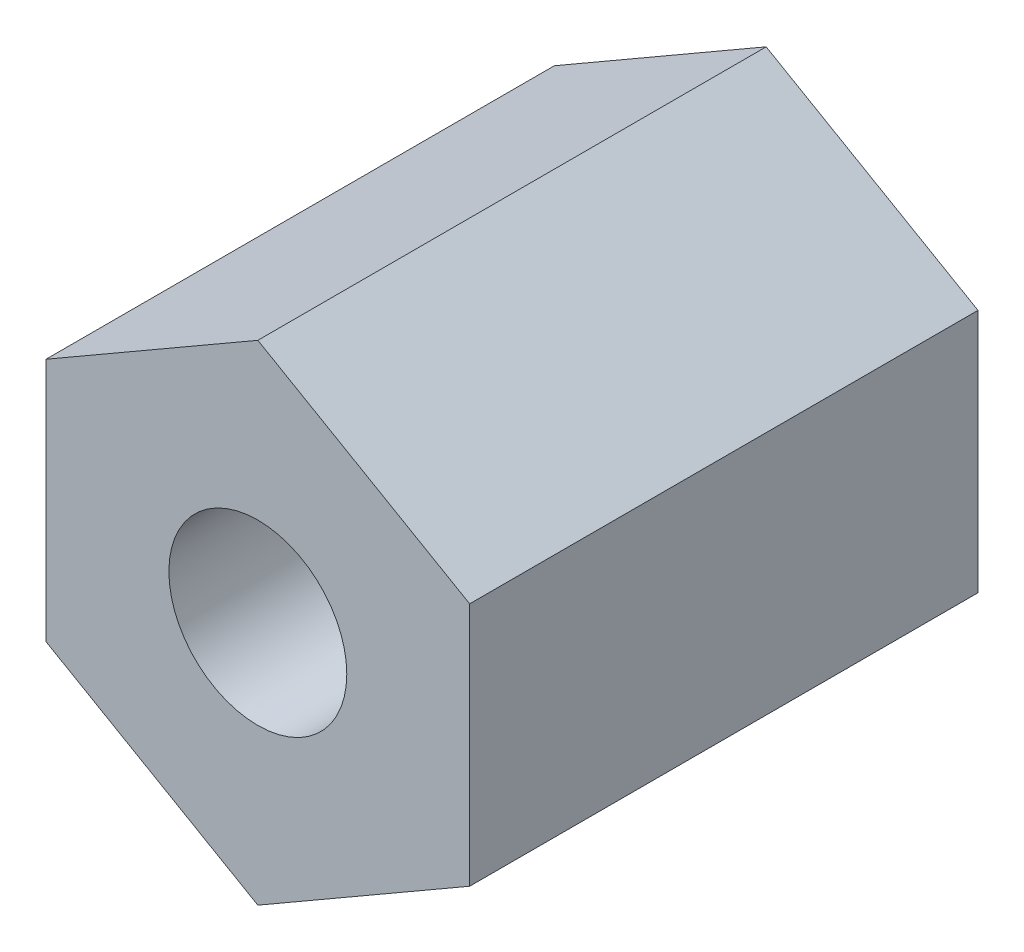
SolidWorks part; units mm, degrees
material "Latón"
ref_plane "Alzado" through (0, 0, 0) normal (0, 0, 1) x (1, 0, 0)
ref_plane "Planta" through (0, 0, 0) normal (0, 1, 0) x (1, 0, 0)
ref_plane "Vista lateral" through (0, 0, 0) normal (1, 0, 0) x (0, 0, -1)
sketch "Croquis1" plane through (0, 0, 0) normal (0, 0, 1) x (1, 0, 0)
  line L0 (-105.9998, -54.5565) -> (-108.5, -53.113)
  line L1 (-108.5, -53.113) -> (-111.0002, -54.5565)
  line L2 (-111.0002, -54.5565) -> (-111.0002, -57.4435)
  line L3 (-111.0002, -57.4435) -> (-108.5, -58.887)
  line L4 (-108.5, -58.887) -> (-105.9998, -57.4435)
  line L5 (-105.9998, -57.4435) -> (-105.9998, -54.5565)
  dimension "D1" = 105.9998
  dimension "D2" = 54.5565
  dimension "D3" = 108.5
  dimension "D4" = 53.113
  dimension "D5" = 111.0002
  dimension "D6" = 54.5565
  dimension "D7" = 111.0002
  dimension "D8" = 57.4435
  dimension "D9" = 108.5
  dimension "D10" = 58.887
  dimension "D11" = 105.9998
  dimension "D12" = 57.4435
extrude "Hex_5" add sketch "Croquis1" along normal blind 6 from offset 12.7
sketch "Croquis2" plane through (0, 0, 0) normal (0, 0, 1) x (1, 0, 0)
  circle A0 centre (-108.5, -56) radius 1.05
  dimension "D1" = 2.1
  dimension "D2" = 108.5
  dimension "D3" = 56
extrude "Rosca_M2-5" cut sketch "Croquis2" along normal blind 6 from offset 12.7
